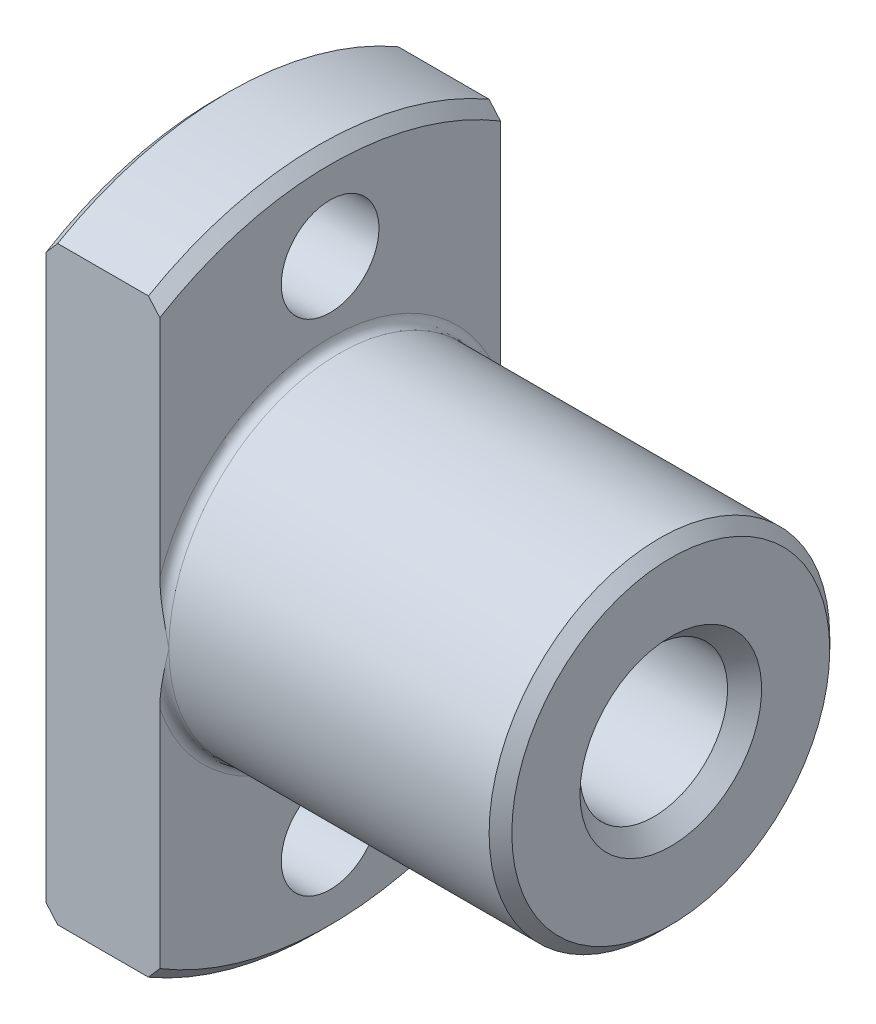
SolidWorks part; units mm, degrees
ref_plane "Front Plane" through (0, 0, 0) normal (0, 0, 1) x (1, 0, 0)
ref_plane "Top Plane" through (0, 0, 0) normal (0, 1, 0) x (1, 0, 0)
ref_plane "Right Plane" through (0, 0, 0) normal (1, 0, 0) x (0, 0, -1)
ref_plane "Plane1" through (0, 0, 0) normal (0, 0, 1) x (1, 0, 0)
sketch "Sketch1" plane through (0, 0, 0) normal (0, 0, 1) x (1, 0, 0)
  line L0 (0, 0) -> (0, 14.5)
  line L1 (0, 14.5) -> (0.5, 15)
  line L2 (0.5, 15) -> (4.5, 15)
  line L3 (4.5, 15) -> (5, 14.5)
  line L4 (5, 14.5) -> (5, 7.9)
  line L5 (5.4, 7.5) -> (19.5, 7.5)
  line L6 (19.5, 7.5) -> (20, 7)
  line L7 (20, 7) -> (20, 0)
  line L8 (20, 0) -> (0, 0)
  line L9 (20, 0) -> (0, 0) construction
  arc A0 (5, 7.9) -> (5.4, 7.5) centre (5.4, 7.9) ccw
revolve "Revolve1" add sketch "Sketch1" angle 360 about L9
ref_plane "Plane2" through (0, 0, 0) normal (0, 0, 1) x (1, 0, 0)
sketch "Sketch2" plane through (0, 0, 0) normal (0, 0, 1) x (1, 0, 0)
  line L0 (0, 0) -> (0, 4)
  line L1 (0, 4) -> (0.75, 3.25)
  line L2 (0.75, 3.25) -> (19.25, 3.25)
  line L3 (19.25, 3.25) -> (20, 4)
  line L4 (20, 4) -> (20, 0)
  line L5 (20, 0) -> (0, 0)
  line L6 (20, 0) -> (0, 0) construction
revolve "Cut-Revolve1" cut sketch "Sketch2" angle 360 about L6
cosmetic thread "Cosmetic Thread1" parameters "D1"=20, "D2"=8
ref_plane "Plane3" through (0, 0, 0) normal (0, 0, 1) x (1, 0, 0)
sketch "Sketch3" plane through (0, 0, 0) normal (0, 0, 1) x (1, 0, 0)
  line L0 (0, 11) -> (0, 13.15)
  line L1 (0, 13.15) -> (5, 13.15)
  line L2 (5, 13.15) -> (5, 11)
  line L3 (5, 11) -> (0, 11)
  line L4 (5, 11) -> (0, 11) construction
revolve "Cut-Revolve2" cut sketch "Sketch3" angle 360 about L4
ref_plane "Plane4" through (0, 0, 0) normal (0, 0, 1) x (1, 0, 0)
sketch "Sketch4" plane through (0, 0, 0) normal (0, 0, 1) x (1, 0, 0)
  line L0 (0, -11) -> (0, -8.85)
  line L1 (0, -8.85) -> (5, -8.85)
  line L2 (5, -8.85) -> (5, -11)
  line L3 (5, -11) -> (0, -11)
  line L4 (5, -11) -> (0, -11) construction
revolve "Cut-Revolve3" cut sketch "Sketch4" angle 360 about L4
ref_plane "Plane5" through (0, 0, 0) normal (1, 0, 0) x (0, 0, -1)
sketch "Sketch5" plane through (0, 0, 0) normal (1, 0, 0) x (0, 0, -1)
  line L0 (-15, -45) -> (15, -45)
  line L1 (15, -45) -> (15, 45)
  line L2 (15, 45) -> (-15, 45)
  line L3 (-15, 45) -> (-15, -45)
  line L4 (-7.5, -30) -> (7.5, -30)
  line L5 (7.5, -30) -> (7.5, 30)
  line L6 (7.5, 30) -> (-7.5, 30)
  line L7 (-7.5, 30) -> (-7.5, -30)
extrude "Cut-Extrude1" cut sketch "Sketch5" against normal blind 7.5 and the other way blind 7.5
